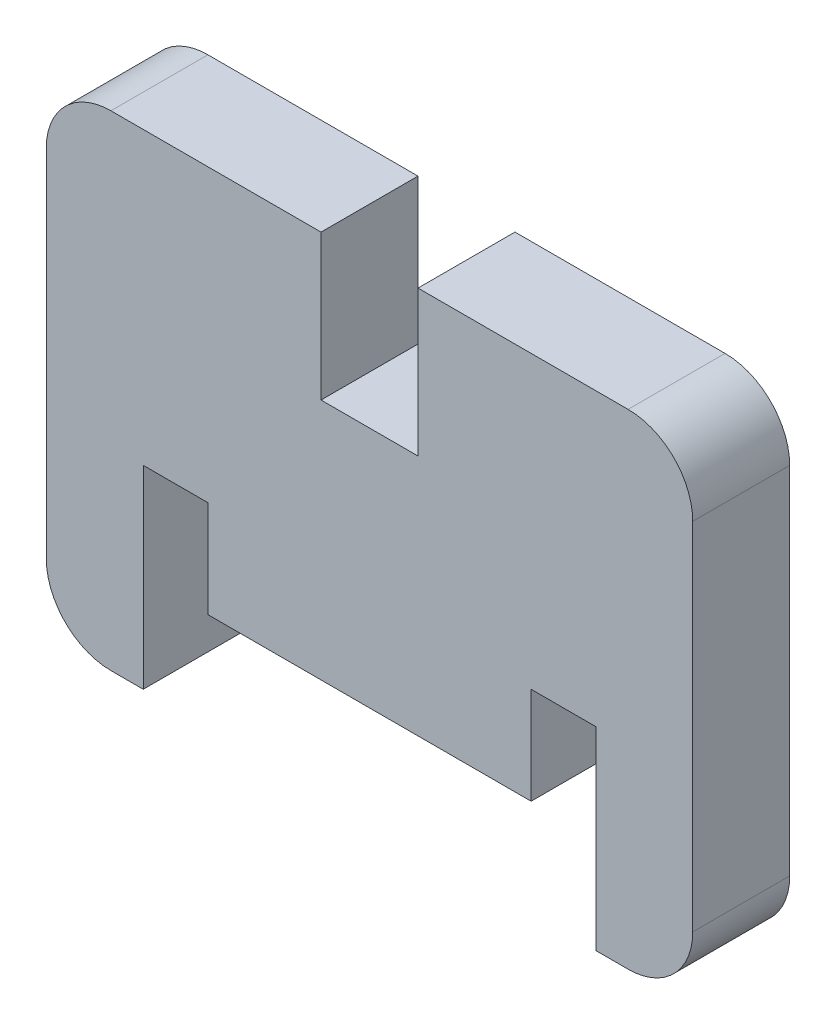
SolidWorks part; units mm, degrees
ref_plane "Plan de face" through (0, 0, 0) normal (0, 0, 1) x (1, 0, 0)
ref_plane "Plan de dessus" through (0, 0, 0) normal (0, 1, 0) x (1, 0, 0)
ref_plane "Plan de droite" through (0, 0, 0) normal (1, 0, 0) x (0, 0, -1)
sketch "Esquisse1" plane through (0, 0, 0) normal (0, 0, 1) x (1, 0, 0)
  line L0 (0, 37.5) -> (0, -37.5) construction
  line L1 (-40, -37.5) -> (40, -37.5)
  line L2 (-50, -27.5) -> (-50, 27.5)
  line L3 (-40, 37.5) -> (40, 37.5)
  line L4 (50, -27.5) -> (50, 27.5)
  line L5 (-50, -37.5) -> (50, 37.5) construction
  line L6 (-50, 37.5) -> (50, -37.5) construction
  line L7 (-50, 0) -> (50, 0) construction
  line L8 (35, -37.5) -> (0, -37.5)
  line L9 (35, -37.5) -> (35, -22.5)
  line L10 (0, -37.5) -> (0, -22.5) construction
  line L11 (35, -22.5) -> (-35, -22.5)
  line L12 (-35, -37.5) -> (-35, -22.5)
  line L13 (0, -7.5) -> (0, 42.9788) construction
  line L14 (-7.5, 15) -> (7.5, 15)
  line L15 (-7.5, 15) -> (-7.5, 37.5)
  line L16 (-7.5, 37.5) -> (7.5, 37.5)
  line L17 (7.5, 15) -> (7.5, 37.5)
  line L18 (-7.5, 15) -> (7.5, 37.5) construction
  line L19 (-7.5, 37.5) -> (7.5, 15) construction
  line L20 (35, -22.5) -> (25, -22.5)
  line L21 (35, -22.5) -> (35, -7.5)
  line L22 (25, -22.5) -> (25, -7.5)
  line L23 (35, -7.5) -> (25, -7.5)
  line L24 (-35, -22.5) -> (-35, -7.5)
  line L25 (-25, -22.5) -> (-25, -7.5)
  line L26 (-35, -7.5) -> (-25, -7.5)
  arc A0 (50, 27.5) -> (40, 37.5) centre (40, 27.5) ccw
  arc A1 (-40, 37.5) -> (-50, 27.5) centre (-40, 27.5) ccw
  arc A2 (-40, -37.5) -> (-50, -27.5) centre (-40, -27.5) cw
  arc A3 (40, -37.5) -> (50, -27.5) centre (40, -27.5) ccw
  point P0 (0, 0)
  point P24 (0, 0)
  dimension "D3" = 10
  dimension "D1" = 100
  dimension "D2" = 75
  dimension "D4" = 15
  dimension "D5" = 15
  dimension "D6" = 22.5
  dimension "D8" = 10
  dimension "D9" = 15
extrude "Boss.-Extru.1" add sketch "Esquisse1" along normal blind 15 contours L1 A3 L4 A0 L3 L17 L14 L15 A1 L2 A2 L12 L11 L9
